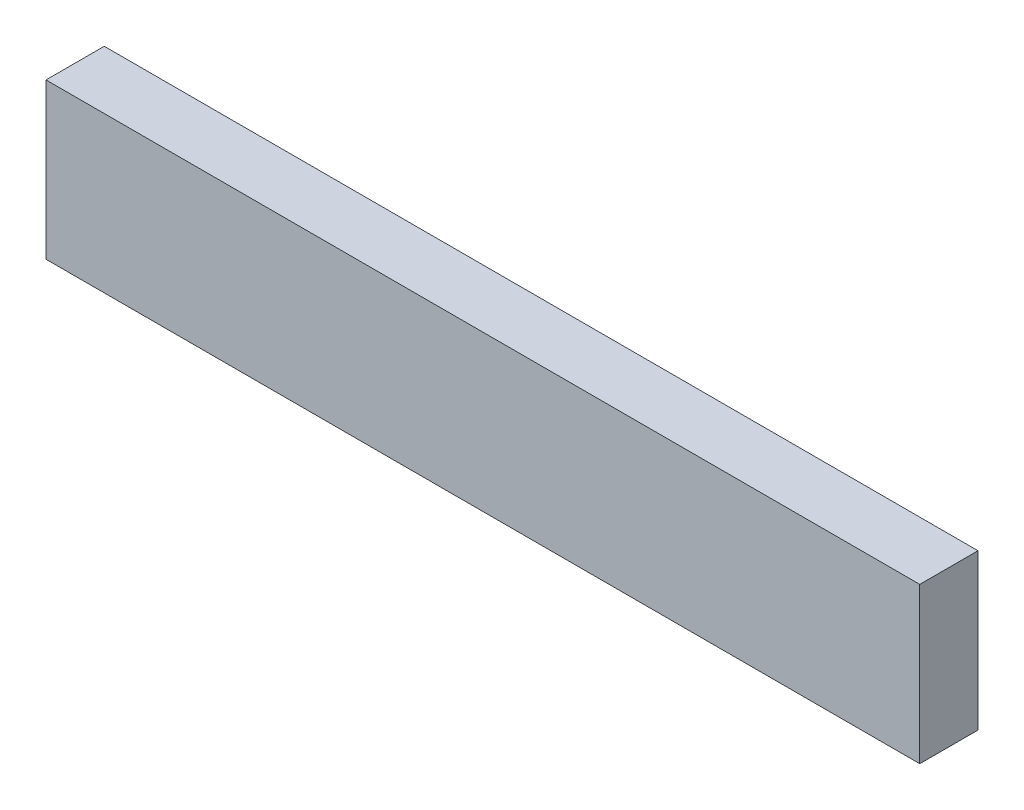
SolidWorks part; units mm, degrees
ref_plane "Front Plane" through (0, 0, 0) normal (0, 0, 1) x (1, 0, 0)
ref_plane "Top Plane" through (0, 0, 0) normal (0, 1, 0) x (1, 0, 0)
ref_plane "Right Plane" through (0, 0, 0) normal (1, 0, 0) x (0, 0, -1)
sketch "Sketch1" plane through (0, 0, 0) normal (0, 0, 1) x (1, 0, 0)
  line L1 (0, 0) -> (45, 0)
  line L2 (0, 0) -> (0, 8)
  line L3 (0, 8) -> (45, 8)
  line L4 (45, 0) -> (45, 8)
  dimension "D1" = 45
  dimension "D2" = 8
extrude "Boss-Extrude1" add sketch "Sketch1" along normal blind 3
